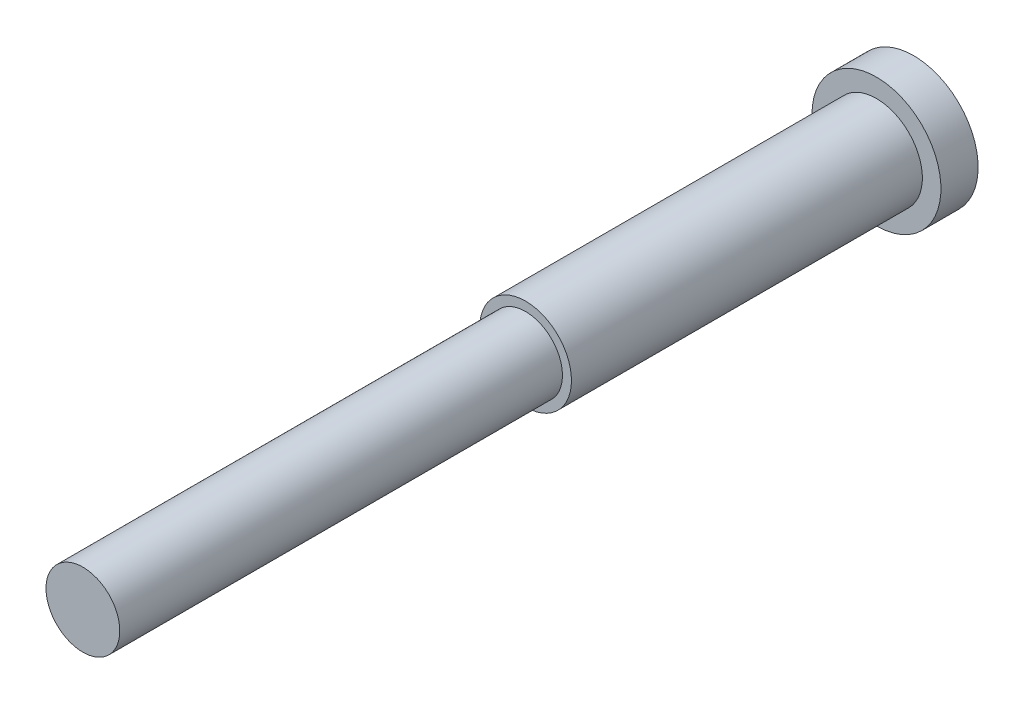
SolidWorks part; units mm, degrees
material "PW20:29:Sc:0:"
ref_plane "Front" through (0, 0, 0) normal (0, 0, 1) x (1, 0, 0)
ref_plane "Top" through (0, 0, 0) normal (0, 1, 0) x (1, 0, 0)
ref_plane "Right" through (0, 0, 0) normal (1, 0, 0) x (0, 0, -1)
sketch "Sketch1" plane through (0, 0, 0) normal (0, 0, 1) x (1, 0, 0)
  circle A0 centre (0, 0) radius 7.9
  dimension "D1" = 15.8
extrude "Base-Extrude" add sketch "Sketch1" along normal blind 60.4
sketch "Sketch2" plane through (0, 0, 60.4) normal (0, 0, 1) x (1, 0, 0)
  circle A0 centre (0, 0) radius 6.35
  dimension "D1" = 12.7
extrude "Boss-Extrude1" add sketch "Sketch2" along normal blind 76.2
sketch "Sketch3" plane through (0, 0, 0) normal (0, 0, -1) x (-1, 0, 0)
  circle A0 centre (0, 0) radius 11.1
  dimension "D1" = 22.2
extrude "Boss-Extrude2" add sketch "Sketch3" along normal blind 6.4
ref_plane "Place" through (0, 0, 53.3) normal (0, 0, 1) x (1, 0, 0)
